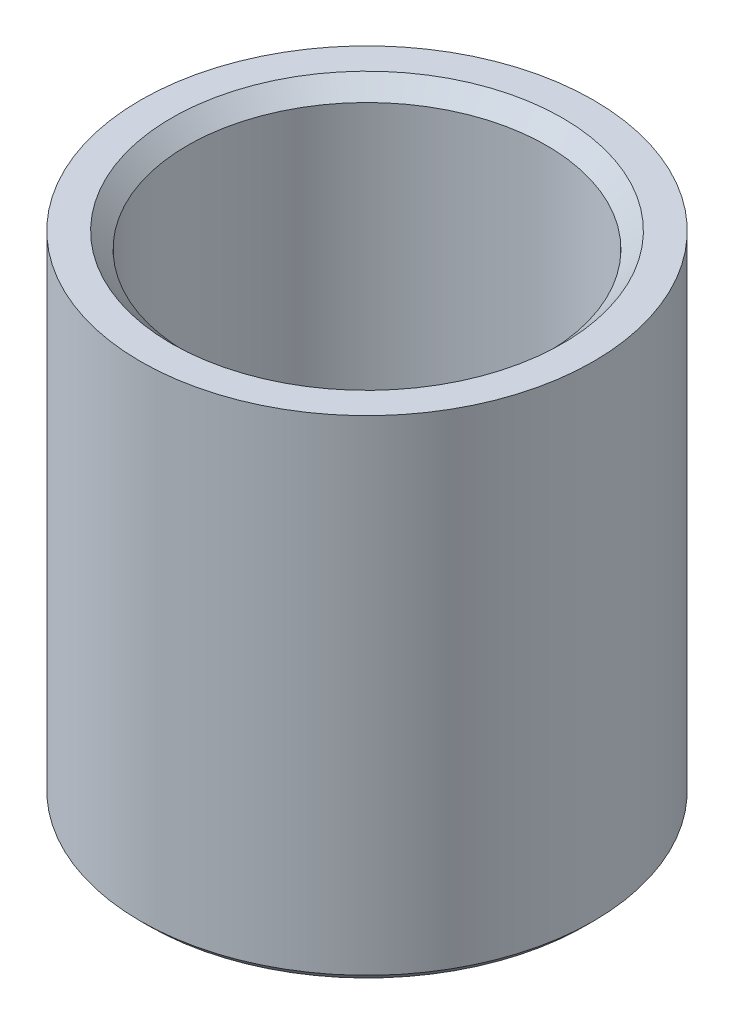
SolidWorks part; units mm, degrees
ref_plane "Front Plane" through (0, 0, 0) normal (0, 0, 1) x (1, 0, 0)
ref_plane "Top Plane" through (0, 0, 0) normal (0, 1, 0) x (1, 0, 0)
ref_plane "Right Plane" through (0, 0, 0) normal (1, 0, 0) x (0, 0, -1)
sketch "Sketch2" plane through (0, 0, 0) normal (0, 1, 0) x (1, 0, 0)
  circle A0 centre (0, 0) radius 28.5
  circle A1 centre (0, 0) radius 22.6
  dimension "D1" = 57
  dimension "D2" = 45.2
extrude "Boss-Extrude1" add sketch "Sketch2" along normal blind 62
chamfer "Chamfer1" distance 2 angle 45 1 edges at (0, 62, 22.6)
chamfer "Chamfer2" distance 1 angle 45 1 edges at (0, 0, 22.6)
chamfer "Chamfer3" distance 1 angle 45 1 edges at (0, 0, 28.5)
